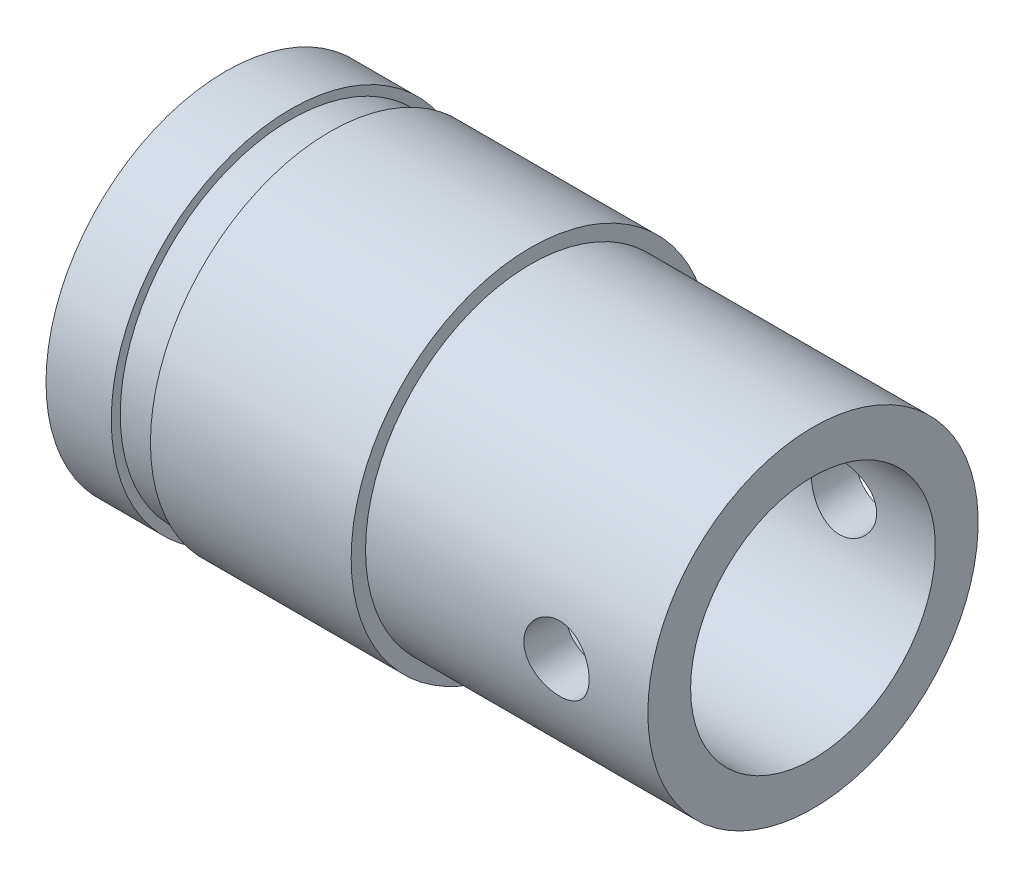
SolidWorks part; units mm, degrees
ref_plane "Plano frontal" through (0, 0, 0) normal (0, 0, 1) x (1, 0, 0)
ref_plane "Plano superior" through (0, 0, 0) normal (0, 1, 0) x (1, 0, 0)
ref_plane "Plano direito" through (0, 0, 0) normal (1, 0, 0) x (0, 0, -1)
sketch "Esboço1" plane through (0, 0, 0) normal (0, 0, 1) x (1, 0, 0)
  line L0 (0, 5.5) -> (2, 5.5)
  line L1 (2, 5.5) -> (2, 5.225)
  line L2 (2, 5.225) -> (3.2, 5.225)
  line L3 (3.2, 5.225) -> (3.2, 5.5)
  line L4 (3.2, 5.5) -> (9.35, 5.5)
  line L5 (9.35, 5.5) -> (9.35, 5.06)
  line L6 (9.35, 5.06) -> (18, 5.06)
  line L7 (18, 5.06) -> (18, 3.75)
  line L8 (0, 0) -> (18, 0) construction
  line L9 (0, 5.5) -> (0, 4.75)
  line L10 (0, 4.75) -> (6.1, 4.75)
  line L11 (6.1, 4.75) -> (6.1, 3.75)
  line L12 (6.1, 3.75) -> (18, 3.75)
  dimension "D1" = 18
  dimension "D2" = 10.12
  dimension "D3" = 11
  dimension "D4" = 10.45
  dimension "D5" = 11
  dimension "D6" = 2
  dimension "D7" = 6.15
  dimension "D8" = 1.2
  dimension "D9" = 9.5
  dimension "D10" = 7.5
  dimension "D11" = 6.1
revolve "Revolução1" add sketch "Esboço1" angle 360 about L8
sketch "Esboço2" plane through (0, 0, 0) normal (0, 0, 1) x (1, 0, 0)
  line L0 (0, 0) -> (18, 0) construction
  line L1 (18, -5.06) -> (18, 5.06) construction
  line L2 (16.2, 0) -> (18, 0) construction
  circle A0 centre (15.2, 0) radius 1
  dimension "D2" = 2
  dimension "D1" = 1.8
extrude "Corte-extrusão1" cut sketch "Esboço2" against normal mid plane 20
